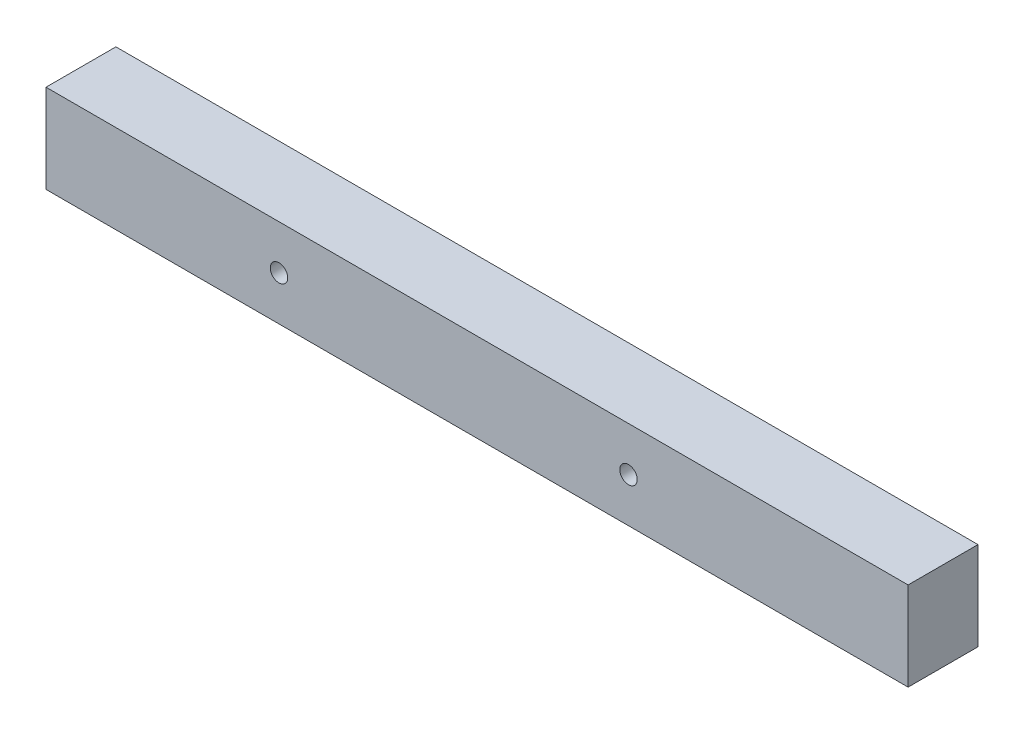
SolidWorks part; units mm, degrees
ref_plane "前视基准面" through (0, 0, 0) normal (0, 0, 1) x (1, 0, 0)
ref_plane "上视基准面" through (0, 0, 0) normal (0, 1, 0) x (1, 0, 0)
ref_plane "右视基准面" through (0, 0, 0) normal (1, 0, 0) x (0, 0, -1)
sketch "草图2" plane through (0, 0, 0) normal (0, 0, 1) x (1, 0, 0)
  line L1 (-37, 1.9) -> (0, 1.9)
  line L2 (-37, 1.9) -> (-37, -1.9)
  line L3 (-37, -1.9) -> (0, -1.9)
  line L7 (0, 1.9) -> (0, -1.9)
  circle A1 centre (-12, 0) radius 0.375
  circle A3 centre (-27, 0) radius 0.375
  dimension "D3" = 0.75
  dimension "D5" = 0.75
  dimension "D4" = 15
  dimension "D1" = 3.8
  dimension "D2" = 1.9
  dimension "D6" = 1.9
  dimension "D7" = 12
  dimension "D8" = 10
extrude "凸台-拉伸1" add sketch "草图2" along normal blind 3
